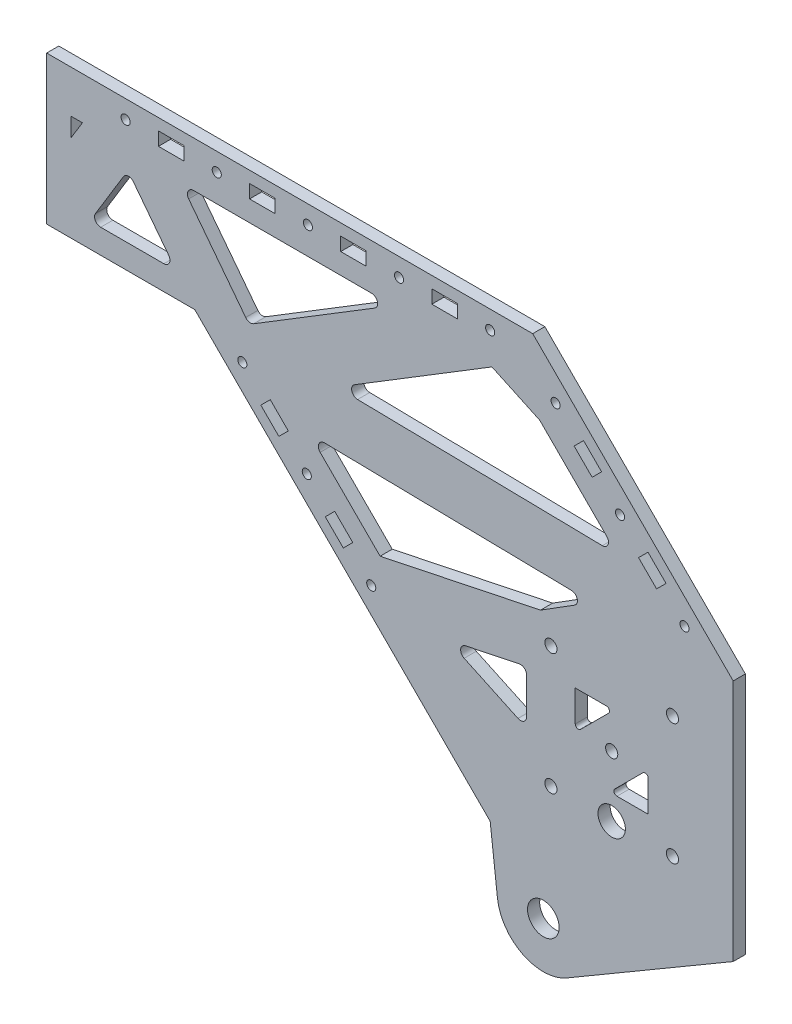
SolidWorks part; units mm, degrees
ref_plane "前视基准面" through (0, 0, 0) normal (0, 0, 1) x (1, 0, 0)
ref_plane "上视基准面" through (0, 0, 0) normal (0, 1, 0) x (1, 0, 0)
ref_plane "右视基准面" through (0, 0, 0) normal (1, 0, 0) x (0, 0, -1)
sketch "草图1" plane through (0, 0, 0) normal (0, 0, 1) x (1, 0, 0)
  line L261 (47.0274, 35.0547) -> (47.0274, 15.0547) construction
  line L315 (47.0274, 15.0547) -> (27.0274, 15.0547) construction
  line L316 (-52.9726, 135.0547) -> (-52.9726, 126.7057) construction
  line L332 (-112.9726, 135.0547) -> (-97.9726, 135.0547) construction
  line L334 (-42.1726, 137.2547) -> (-33.7726, 137.2547)
  line L335 (-42.1726, 137.2547) -> (-42.1726, 132.8547)
  line L336 (-42.1726, 132.8547) -> (-33.7726, 132.8547)
  line L337 (-33.7726, 137.2547) -> (-33.7726, 132.8547)
  line L338 (-42.1726, 137.2547) -> (-33.7726, 132.8547) construction
  line L339 (-42.1726, 132.8547) -> (-33.7726, 137.2547) construction
  line L389 (-138.9726, 141.0547) -> (21.0274, 141.0547)
  line L390 (-22.9726, 135.0547) -> (-22.9726, 144.5851) construction
  line L395 (-37.9726, 135.0547) -> (-7.9726, 135.0547) construction
  line L418 (87.0274, 75.0547) -> (21.0274, 141.0547)
  line L419 (-3.7726, 132.8547) -> (-12.1726, 137.2547) construction
  line L420 (-3.7726, 137.2547) -> (-12.1726, 132.8547) construction
  line L421 (7.0274, 135.0547) -> (-7.9726, 135.0547) construction
  line L422 (-12.1726, 137.2547) -> (-12.1726, 132.8547)
  line L423 (-3.7726, 132.8547) -> (-12.1726, 132.8547)
  line L424 (-3.7726, 137.2547) -> (-3.7726, 132.8547)
  line L443 (-3.7726, 137.2547) -> (-12.1726, 137.2547)
  line L444 (-102.1726, 137.2547) -> (-93.7726, 132.8547) construction
  line L445 (-102.1726, 132.8547) -> (-93.7726, 137.2547) construction
  line L446 (7.0274, -4.9453) -> (-138.9726, 141.0547) construction
  line L447 (-67.9726, 135.0547) -> (-97.9726, 135.0547) construction
  line L448 (47.0274, 15.0547) -> (24.5274, -23.9164) construction
  line L449 (-63.7726, 132.8547) -> (-72.1726, 137.2547) construction
  line L483 (-63.7726, 137.2547) -> (-72.1726, 132.8547) construction
  line L515 (47.0274, 35.0547) -> (47.0274, 135.0547) construction
  line L516 (47.0274, 135.0547) -> (-52.9726, 135.0547) construction
  line L517 (-102.1726, 137.2547) -> (-93.7726, 137.2547)
  line L518 (-102.1726, 137.2547) -> (-102.1726, 132.8547)
  line L519 (-102.1726, 132.8547) -> (-93.7726, 132.8547)
  line L520 (-93.7726, 137.2547) -> (-93.7726, 132.8547)
  line L521 (-72.1726, 137.2547) -> (-72.1726, 132.8547)
  line L522 (-63.7726, 132.8547) -> (-72.1726, 132.8547)
  line L523 (-63.7726, 137.2547) -> (-63.7726, 132.8547)
  line L524 (-63.7726, 137.2547) -> (-72.1726, 137.2547)
  line L525 (7.0274, -4.9453) -> (9.4285, -25.666)
  line L551 (7.0274, -4.9453) -> (87.0274, -4.9453) construction
  line L552 (7.0274, -4.9453) -> (7.0274, 75.0547) construction
  line L553 (7.0274, 75.0547) -> (87.0274, 75.0547) construction
  line L554 (87.0274, -4.9453) -> (87.0274, 75.0547)
  line L555 (87.0274, -4.9453) -> (32.2059, -37.0344)
  line L556 (21.4033, 132.1936) -> (81.3921, 72.2048) construction
  line L557 (54.0274, 108.0547) -> (35.0674, 89.0947) construction
  line L558 (43.7037, 113.0045) -> (34.6527, 115.8329) construction
  line L559 (55.8659, 94.6197) -> (61.8056, 88.68)
  line L576 (55.8659, 94.6197) -> (58.9772, 97.731)
  line L577 (58.9772, 97.731) -> (64.9169, 91.7913)
  line L578 (61.8056, 88.68) -> (64.9169, 91.7913)
  line L579 (55.8659, 94.6197) -> (64.9169, 91.7913) construction
  line L580 (58.9772, 97.731) -> (61.8056, 88.68) construction
  line L581 (40.5924, 109.8932) -> (37.764, 118.9442) construction
  line L582 (34.6527, 115.8329) -> (37.764, 118.9442)
  line L583 (43.7037, 113.0045) -> (37.764, 118.9442)
  line L584 (40.5924, 109.8932) -> (43.7037, 113.0045)
  line L585 (40.5924, 109.8932) -> (34.6527, 115.8329)
  line L586 (60.3914, 93.2055) -> (58.8358, 91.6499) construction
  line L587 (39.1782, 114.4187) -> (37.6226, 112.8631) construction
  line L588 (-138.9726, 141.0547) -> (-138.9726, 92.2861)
  line L589 (14.0274, 68.0547) -> (9.4285, 72.6537) construction
  line L594 (47.0274, 15.0547) -> (67.0274, 15.0547) construction
  line L599 (67.0274, 15.0547) -> (67.0274, 55.0547) construction
  line L600 (67.0274, 55.0547) -> (27.0274, 55.0547) construction
  line L605 (-25.9726, 28.0547) -> (-21.7299, 32.2974) construction
  line L606 (-138.9726, 92.2861) -> (-90.2039, 92.2861)
  line L607 (-81.7187, 92.2861) -> (-21.7299, 32.2974) construction
  line L608 (-90.2039, 92.2861) -> (7.0274, -4.9453)
  line L609 (-59.4183, 73.097) -> (-68.4693, 75.9255) construction
  line L610 (-47.2561, 54.7123) -> (-41.3164, 48.7726)
  line L611 (-47.2561, 54.7123) -> (-44.1448, 57.8235)
  line L612 (-44.1448, 57.8235) -> (-38.2051, 51.8838)
  line L613 (-41.3164, 48.7726) -> (-38.2051, 51.8838)
  line L614 (-47.2561, 54.7123) -> (-38.2051, 51.8838) construction
  line L615 (-44.1448, 57.8235) -> (-41.3164, 48.7726) construction
  line L616 (-62.5296, 69.9858) -> (-65.358, 79.0367) construction
  line L617 (-68.4693, 75.9255) -> (-65.358, 79.0367)
  line L618 (-59.4183, 73.097) -> (-65.358, 79.0367)
  line L619 (-62.5296, 69.9858) -> (-59.4183, 73.097)
  line L620 (-62.5296, 69.9858) -> (-68.4693, 75.9255)
  line L621 (-42.7306, 53.298) -> (-44.2862, 51.7424) construction
  line L622 (-63.9438, 74.5112) -> (-65.4994, 72.9556) construction
  circle A39 centre (-52.9726, 135.0547) radius 1.5
  circle A42 centre (47.0274, 15.0547) radius 4.5
  circle A49 centre (-22.9726, 135.0547) radius 1.5
  circle A69 centre (7.0274, 135.0547) radius 1.5
  circle A71 centre (67.0274, 15.0547) radius 2
  circle A77 centre (67.0274, 55.0547) radius 2
  circle A89 centre (27.0274, 55.0547) radius 2
  circle A90 centre (27.0274, 15.0547) radius 2
  circle A91 centre (47.0274, 35.0547) radius 2
  circle A92 centre (-112.9726, 135.0547) radius 1.5
  circle A93 centre (-82.9726, 135.0547) radius 1.5
  circle A94 centre (24.5274, -23.9164) radius 5.2
  circle A96 centre (24.5274, -23.9164) radius 15.2 construction
  arc A97 (9.4285, -25.666) -> (32.2059, -37.0344) centre (24.5274, -23.9164) ccw
  circle A98 centre (49.7848, 103.8121) radius 1.5
  circle A99 centre (70.998, 82.5989) radius 1.5
  circle A100 centre (28.5716, 125.0253) radius 1.5
  circle A104 centre (-53.3372, 63.9046) radius 1.5
  circle A105 centre (-32.124, 42.6914) radius 1.5
  circle A106 centre (-74.5504, 85.1178) radius 1.5
  point P5 (210.9534, 218.4629)
  point P6 (288.6284, 218.4629)
  point P54 (-105.4726, 135.0547)
  point P60 (60.3914, 93.2055)
  point P92 (-42.7306, 53.298)
  dimension "D1" = 40
  dimension "D3" = 20
  dimension "D5" = 40
  dimension "D4" = 20
  dimension "D6" = 40
  dimension "D2" = 40
  dimension "D7" = 60
  dimension "D12" = 3
  dimension "D19" = 10.4
  dimension "D20" = 10
  dimension "D22" = 3
  dimension "D8" = 3
  dimension "D9" = 15
  dimension "D10" = 15
  dimension "D11" = 8.4
  dimension "D13" = 4.4
  dimension "D14" = 6
  dimension "D15" = 45
  dimension "D16" = 15
  dimension "D17" = 8.4
  dimension "D18" = 45
  dimension "D21" = 6
  dimension "D23" = 15
  dimension "D24" = 8.4
  dimension "D25" = 4.4
  dimension "D26" = 4.4
extrude "凸台-拉伸1" add sketch "草图1" along normal blind 4
sketch "草图2" plane through (0, 0, 0) normal (0, 0, -1) x (-1, 0, 0)
  line L0 (74.5504, 85.1178) -> (32.124, 42.6914) construction
  line L1 (32.124, 42.6914) -> (-27.0274, 15.0547) construction
  line L2 (-27.0274, 15.0547) -> (-27.0274, 55.0547) construction
  line L3 (-27.0274, 55.0547) -> (-70.998, 82.5989) construction
  line L5 (-7.0274, 135.0547) -> (112.9726, 135.0547) construction
  line L6 (112.9726, 135.0547) -> (138.9726, 92.2861) construction
  line L8 (74.5504, 85.1178) -> (112.9726, 135.0547) construction
  line L9 (138.9726, 92.2861) -> (90.2039, 92.2861) construction
  line L10 (90.2039, 92.2861) -> (74.5504, 85.1178) construction
  line L11 (98.7922, 103.5057) -> (110.419, 118.6169)
  line L12 (113.7131, 118.4362) -> (122.8995, 103.325)
  line L13 (121.1905, 100.2861) -> (100.3774, 100.2861)
  line L14 (52.4384, 75.7338) -> (-40.5172, 74.1251) construction
  line L15 (112.9726, 135.0547) -> (138.9726, 135.0547) construction
  line L16 (138.9726, 141.0547) -> (138.9726, 92.2861) construction
  line L17 (138.9726, 135.0547) -> (138.9726, 92.2861) construction
  line L18 (1.5409, 37.2325) -> (-16.1808, 28.9526)
  line L19 (-19.0274, 30.7646) -> (-19.0274, 42.7485)
  line L20 (1.1035, 41.0022) -> (-16.6182, 44.7062)
  line L21 (-19.0274, 27.6226) -> (-19.0274, 45.2098) construction
  line L22 (6.9802, 39.7739) -> (-19.0274, 45.2098) construction
  line L23 (6.9802, 39.7739) -> (-19.0274, 27.6226) construction
  line L24 (96.315, 100.2861) -> (112.1978, 120.9288) construction
  line L25 (112.1978, 120.9288) -> (124.7469, 100.2861) construction
  line L26 (127.1982, 127.0547) -> (130.9726, 120.8462)
  line L27 (130.9726, 127.0547) -> (130.9726, 120.8462)
  line L28 (127.1982, 127.0547) -> (130.9726, 127.0547)
  line L29 (74.5504, 85.1178) -> (-7.0274, 135.0547) construction
  line L30 (124.7469, 100.2861) -> (96.315, 100.2861) construction
  line L31 (-23.6122, 63.5354) -> (-40.5172, 74.1251) construction
  line L32 (52.4384, 75.7338) -> (29.2014, 52.4968) construction
  line L33 (-23.3319, 117.5371) -> (-48.886, 91.9829) construction
  line L34 (43.4854, 93.5816) -> (-48.886, 91.9829) construction
  line L35 (43.4854, 93.5816) -> (-7.6073, 124.8574) construction
  line L36 (24.9136, 126.0547) -> (94.6921, 126.0547) construction
  line L37 (72.3501, 97.0171) -> (24.9136, 126.0547) construction
  line L38 (73.4463, 98.4417) -> (92.2149, 122.8351)
  line L39 (32.0116, 126.0547) -> (90.6298, 126.0547)
  line L40 (70.817, 97.9555) -> (30.9675, 122.349)
  line L41 (74.5504, 85.1178) -> (-70.998, 82.5989) construction
  line L42 (-7.0274, 135.0547) -> (-28.5716, 125.0253) construction
  line L43 (-28.5716, 125.0253) -> (-70.998, 82.5989) construction
  line L44 (36.6167, 93.4627) -> (-43.9377, 92.0686)
  line L45 (-23.3319, 117.5371) -> (-45.3865, 95.4825)
  line L46 (-7.6073, 124.8574) -> (-23.3319, 117.5371)
  line L47 (37.6263, 97.1682) -> (-7.6073, 124.8574)
  line L48 (32.124, 42.6914) -> (-27.0274, 55.0547) construction
  line L49 (29.2014, 52.4968) -> (-23.6122, 63.5354)
  line L50 (-23.6122, 63.5354) -> (-34.8054, 70.5471)
  line L51 (47.4901, 75.6482) -> (-33.7783, 74.2417)
  line L52 (48.9389, 72.2343) -> (29.2014, 52.4968)
  line L53 (96.315, 100.2861) -> (96.315, 100.2861) construction
  line L54 (72.3501, 97.0171) -> (94.6921, 126.0547) construction
  line L55 (-27.0274, 15.0547) -> (-67.0274, 55.0547) construction
  line L56 (-67.0274, 55.0547) -> (-67.0274, 15.0547) construction
  line L57 (-67.0274, 15.0547) -> (-27.0274, 15.0547) construction
  line L58 (-59.0274, 23.0547) -> (-48.7554, 23.0547)
  line L59 (-48.0482, 24.7618) -> (-57.3203, 34.0339)
  line L60 (-59.0274, 33.3268) -> (-59.0274, 23.0547)
  line L61 (-27.0274, 55.0547) -> (-67.0274, 55.0547) construction
  line L62 (-35.0274, 36.7827) -> (-35.0274, 47.0547)
  line L63 (-35.0274, 47.0547) -> (-45.2995, 47.0547)
  line L64 (-36.7345, 36.0756) -> (-46.0066, 45.3476)
  line L65 (-59.0274, 35.741) -> (-59.0274, 23.0547) construction
  line L66 (-46.3411, 23.0547) -> (-59.0274, 35.741) construction
  line L67 (-59.0274, 23.0547) -> (-46.3411, 23.0547) construction
  line L68 (-35.0274, 47.0547) -> (-47.7137, 47.0547) construction
  line L69 (-35.0274, 34.3684) -> (-47.7137, 47.0547) construction
  line L70 (-35.0274, 34.3684) -> (-35.0274, 47.0547) construction
  arc A0 (-19.0274, 42.7485) -> (-16.6182, 44.7062) centre (-17.0274, 42.7485) cw
  arc A1 (-19.0274, 30.7646) -> (-16.1808, 28.9526) centre (-17.0274, 30.7646) ccw
  arc A2 (110.419, 118.6169) -> (113.7131, 118.4362) centre (112.0041, 117.3973) cw
  arc A3 (98.7922, 103.5057) -> (100.3774, 100.2861) centre (100.3774, 102.2861) ccw
  arc A4 (121.1905, 100.2861) -> (122.8995, 103.325) centre (121.1905, 102.2861) ccw
  arc A5 (1.1035, 41.0022) -> (1.5409, 37.2325) centre (0.6943, 39.0445) cw
  arc A6 (-33.7783, 74.2417) -> (-34.8054, 70.5471) centre (-33.7437, 72.242) ccw
  arc A7 (47.4901, 75.6482) -> (48.9389, 72.2343) centre (47.5247, 73.6485) cw
  arc A8 (-45.3865, 95.4825) -> (-43.9377, 92.0686) centre (-43.9723, 94.0683) ccw
  arc A9 (36.6167, 93.4627) -> (37.6263, 97.1682) centre (36.5821, 95.4624) ccw
  arc A10 (32.0116, 126.0547) -> (30.9675, 122.349) centre (32.0116, 124.0547) ccw
  arc A11 (90.6298, 126.0547) -> (92.2149, 122.8351) centre (90.6298, 124.0547) cw
  arc A12 (70.817, 97.9555) -> (73.4463, 98.4417) centre (71.8612, 99.6613) ccw
  arc A13 (-59.0274, 33.3268) -> (-57.3203, 34.0339) centre (-58.0274, 33.3268) cw
  arc A14 (-48.7554, 23.0547) -> (-48.0482, 24.7618) centre (-48.7554, 24.0547) ccw
  arc A15 (-45.2995, 47.0547) -> (-46.0066, 45.3476) centre (-45.2995, 46.0547) ccw
  arc A16 (-36.7345, 36.0756) -> (-35.0274, 36.7827) centre (-36.0274, 36.7827) ccw
  dimension "D7" = 2
  dimension "D10" = 1
  dimension "D1" = 8
  dimension "D2" = 8
  dimension "D3" = 9
  dimension "D4" = 9
  dimension "D5" = 9
  dimension "D6" = 8
  dimension "D8" = 8
  dimension "D9" = 8
extrude "切除-拉伸1" cut sketch "草图2" against normal blind 10
